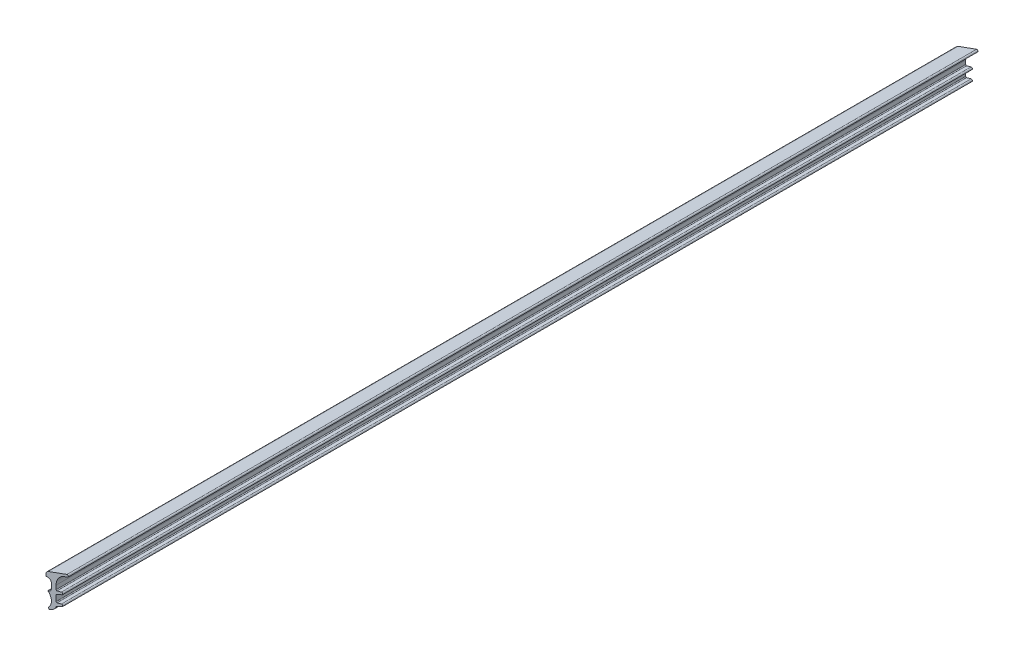
SolidWorks part; units mm, degrees
material "Silicon Rubber"
ref_plane "Front Plane" through (0, 0, 0) normal (0, 0, 1) x (1, 0, 0)
ref_plane "Top Plane" through (0, 0, 0) normal (0, 1, 0) x (1, 0, 0)
ref_plane "Right Plane" through (0, 0, 0) normal (1, 0, 0) x (0, 0, -1)
sketch "Sketch1" plane through (0, 0, 0) normal (0, 0, 1) x (1, 0, 0)
  line L0 (2.3225, -4.6884) -> (2.3225, -1.819)
  line L1 (2.5397, -1.4903) -> (5.3007, -0.314)
  line L2 (4.9491, 0.696) -> (2.7741, 0.1005)
  line L3 (2.3225, 0.4451) -> (2.3225, 2.3527)
  line L4 (6.2751, 7.9975) -> (8.0676, 8.6499)
  line L5 (7.7009, 9.6572) -> (-1.5043, 6.3068)
  line L6 (-2.6798, 4.628) -> (-2.6798, 3.7351)
  line L7 (-2.6798, 3.7351) -> (-1.7865, 3.7351)
  line L8 (0, 1.9486) -> (0, -0.292)
  line L9 (2.5397, -6.6238) -> (5.3007, -5.4475)
  line L10 (4.9491, -4.4375) -> (2.7741, -5.033)
  arc A0 (2.3225, -4.6884) -> (2.7741, -5.033) centre (2.6798, -4.6884) ccw
  arc A1 (2.5397, -1.4903) -> (2.3225, -1.819) centre (2.6798, -1.819) ccw
  arc A2 (5.3007, -0.314) -> (4.9491, 0.696) centre (5.0907, 0.1791) ccw
  arc A3 (2.3225, 0.4451) -> (2.7741, 0.1005) centre (2.6798, 0.4451) ccw
  arc A4 (6.2751, 7.9975) -> (2.3225, 2.3527) centre (8.3296, 2.3527) ccw
  arc A5 (8.0676, 8.6499) -> (7.7009, 9.6572) centre (7.8843, 9.1536) ccw
  arc A6 (-1.5043, 6.3068) -> (-2.6798, 4.628) centre (-0.8933, 4.628) ccw
  arc A7 (0, 1.9486) -> (-1.7865, 3.7351) centre (-1.7865, 1.9486) ccw
  arc A8 (-1.7865, -2.0785) -> (0, -0.292) centre (-1.7865, -0.292) ccw
  arc A9 (-1.348, -8.7971) -> (-1.7865, -2.0785) centre (-4.3838, -5.6216) ccw
  arc A10 (-1.348, -8.7971) -> (-0.83, -9.6997) centre (-0.9777, -9.1845) ccw
  arc A11 (-0.83, -9.6997) -> (2.3225, -6.9525) centre (-2.1891, -4.9578) ccw
  arc A12 (2.5397, -6.6238) -> (2.3225, -6.9525) centre (2.6798, -6.9525) ccw
  arc A13 (5.3007, -5.4475) -> (4.9491, -4.4375) centre (5.0907, -4.9544) ccw
  point P40 (8.4202, 9.1536)
  point P41 (7.8843, 9.6895)
  point P42 (-0.9777, -9.7205)
  point P52 (0, -5.3355)
  dimension "D6" = 4.9329
  dimension "D10" = 110
  dimension "D12" = 74.688
  dimension "D15" = 0.9777
  dimension "D16" = 2.7682
  dimension "D18" = 0.8929
  dimension "D1" = 0.3573
  dimension "D2" = 0.536
  dimension "D3" = 6.0071
  dimension "D4" = 1.7865
  dimension "D5" = 4.3931
  dimension "D7" = 2.3225
  dimension "D11" = 113.076
  dimension "D13" = 2.6798
  dimension "D14" = 5.1335
  dimension "D35" = 3.7351
  dimension "Height" = 19.41
  dimension "Width" = 11.1
sketch "Sketch2" plane through (0, 0, 0) normal (1, 0, 0) x (0, 0, -1)
  line L0 (-999.75, 0) -> (999.75, 0) construction
  point P4 (0, 0)
  point P6 (-999.75, 0)
  point P7 (999.75, 0)
  dimension "Length" = 1999.5
sketch "Sketch3" plane through (0, 0, 0) normal (0, 0, 1) x (1, 0, 0)
  line L11 (0, 1.9486) -> (0, -0.292)
  line L12 (2.5397, -6.6238) -> (5.3007, -5.4475)
  line L13 (4.9491, -4.4375) -> (2.7741, -5.033)
  line L14 (2.3225, -4.6884) -> (2.3225, -1.819)
  line L15 (2.5397, -1.4903) -> (5.3007, -0.314)
  line L16 (4.9491, 0.696) -> (2.7741, 0.1005)
  line L17 (2.3225, 0.4451) -> (2.3225, 2.3527)
  line L18 (6.2751, 7.9975) -> (8.0676, 8.6499)
  line L19 (7.7009, 9.6572) -> (-1.5043, 6.3068)
  line L20 (-2.6798, 4.628) -> (-2.6798, 3.7351)
  line L21 (-2.6798, 3.7351) -> (-1.7865, 3.7351)
  line L22 (0, 1.9486) -> (0, -0.292)
  line L23 (2.5397, -6.6238) -> (5.3007, -5.4475)
  line L24 (4.9491, -4.4375) -> (2.7741, -5.033)
  line L25 (2.3225, -4.6884) -> (2.3225, -1.819)
  line L26 (2.5397, -1.4903) -> (5.3007, -0.314)
  line L27 (4.9491, 0.696) -> (2.7741, 0.1005)
  line L28 (2.3225, 0.4451) -> (2.3225, 2.3527)
  line L29 (6.2751, 7.9975) -> (8.0676, 8.6499)
  line L30 (7.7009, 9.6572) -> (-1.5043, 6.3068)
  line L31 (-2.6798, 4.628) -> (-2.6798, 3.7351)
  line L32 (-2.6798, 3.7351) -> (-1.7865, 3.7351)
  arc A14 (-1.7865, -2.0785) -> (0, -0.292) centre (-1.7865, -0.292) ccw
  arc A15 (-1.348, -8.7971) -> (-1.7865, -2.0785) centre (-4.3838, -5.6216) ccw
  arc A16 (-1.348, -8.7971) -> (-0.83, -9.6997) centre (-0.9777, -9.1845) ccw
  arc A17 (-0.83, -9.6997) -> (2.3225, -6.9525) centre (-2.1891, -4.9578) ccw
  arc A18 (2.5397, -6.6238) -> (2.3225, -6.9525) centre (2.6798, -6.9525) ccw
  arc A19 (5.3007, -5.4475) -> (4.9491, -4.4375) centre (5.0907, -4.9544) ccw
  arc A20 (2.3225, -4.6884) -> (2.7741, -5.033) centre (2.6798, -4.6884) ccw
  arc A21 (2.5397, -1.4903) -> (2.3225, -1.819) centre (2.6798, -1.819) ccw
  arc A22 (5.3007, -0.314) -> (4.9491, 0.696) centre (5.0907, 0.1791) ccw
  arc A23 (2.3225, 0.4451) -> (2.7741, 0.1005) centre (2.6798, 0.4451) ccw
  arc A24 (6.2751, 7.9975) -> (2.3225, 2.3527) centre (8.3296, 2.3527) ccw
  arc A25 (8.0676, 8.6499) -> (7.7009, 9.6572) centre (7.8843, 9.1536) ccw
  arc A26 (-1.5043, 6.3068) -> (-2.6798, 4.628) centre (-0.8933, 4.628) ccw
  arc A27 (0, 1.9486) -> (-1.7865, 3.7351) centre (-1.7865, 1.9486) ccw
  arc A28 (-1.7865, -2.0785) -> (0, -0.292) centre (-1.7865, -0.292) ccw
  arc A29 (-1.348, -8.7971) -> (-1.7865, -2.0785) centre (-4.3838, -5.6216) ccw
  arc A30 (-1.348, -8.7971) -> (-0.83, -9.6997) centre (-0.9777, -9.1845) ccw
  arc A31 (-0.83, -9.6997) -> (2.3225, -6.9525) centre (-2.1891, -4.9578) ccw
  arc A32 (2.5397, -6.6238) -> (2.3225, -6.9525) centre (2.6798, -6.9525) ccw
  arc A33 (5.3007, -5.4475) -> (4.9491, -4.4375) centre (5.0907, -4.9544) ccw
  arc A34 (2.3225, -4.6884) -> (2.7741, -5.033) centre (2.6798, -4.6884) ccw
  arc A35 (2.5397, -1.4903) -> (2.3225, -1.819) centre (2.6798, -1.819) ccw
  arc A36 (5.3007, -0.314) -> (4.9491, 0.696) centre (5.0907, 0.1791) ccw
  arc A37 (2.3225, 0.4451) -> (2.7741, 0.1005) centre (2.6798, 0.4451) ccw
  arc A38 (6.2751, 7.9975) -> (2.3225, 2.3527) centre (8.3296, 2.3527) ccw
  arc A39 (8.0676, 8.6499) -> (7.7009, 9.6572) centre (7.8843, 9.1536) ccw
  arc A40 (-1.5043, 6.3068) -> (-2.6798, 4.628) centre (-0.8933, 4.628) ccw
  arc A41 (0, 1.9486) -> (-1.7865, 3.7351) centre (-1.7865, 1.9486) ccw
  dimension "D1" = 0
extrude "Boss-Extrude1" add sketch "Sketch3" along normal mid plane 451.58
ref_plane "Plane1" through (4.2996, -1.5832, 0) normal (-0.9384, 0.3455, 0) x (0, 0, 1)
sketch "Sketch4" plane through (4.2996, -1.5832, 0) normal (-0.9384, 0.3455, 0) x (0, 0, 1)
  line L0 (-225.79, 3.417) -> (-217.357, 11.85)
  line L1 (225.79, 11.85) -> (-225.79, 11.85) construction
  line L2 (-217.357, 11.85) -> (-225.79, 11.85)
  line L3 (-225.79, 11.85) -> (-225.79, 3.417)
  dimension "D1" = 45
extrude "Cut-Extrude1" [suppressed] cut sketch "Sketch4" along normal through all and the other way through all
sketch "Sketch5" plane through (4.2996, -1.5832, 0) normal (-0.9384, 0.3455, 0) x (0, 0, 1)
  line L0 (225.79, 3.417) -> (217.357, 11.85)
  line L1 (225.79, 11.85) -> (-225.79, 11.85) construction
  line L2 (217.357, 11.85) -> (225.79, 11.85)
  line L3 (225.79, 11.85) -> (225.79, 3.417)
  dimension "D1" = 45
extrude "Cut-Extrude2" [suppressed] cut sketch "Sketch5" against normal through all and the other way through all
